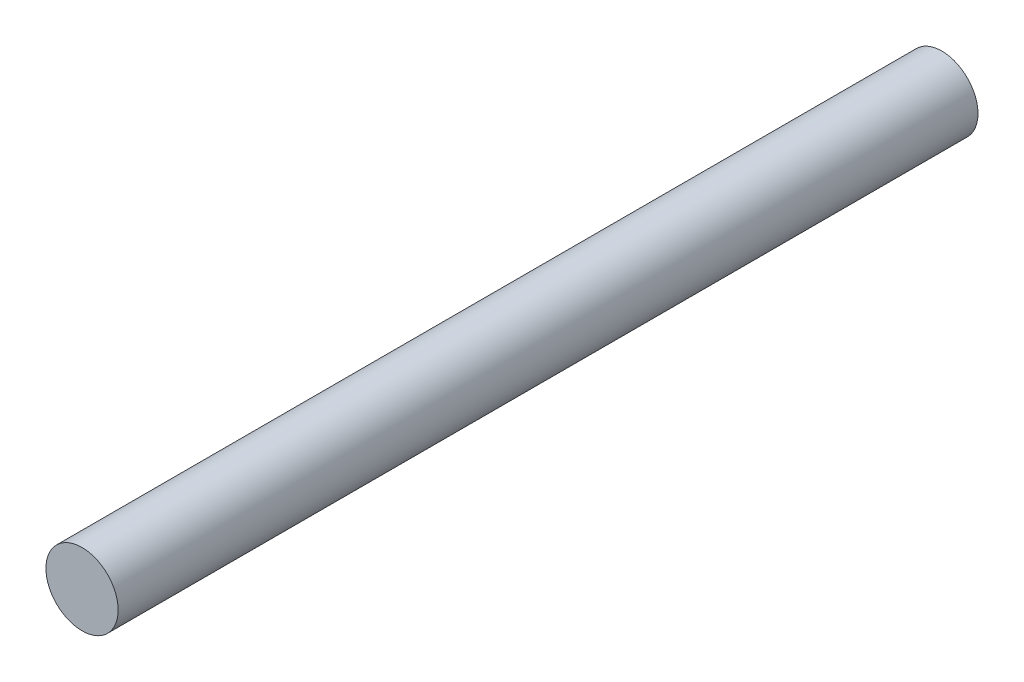
SolidWorks part; units mm, degrees
ref_plane "Piano frontale" through (0, 0, 0) normal (1, 0, 0) x (0, 1, 0)
ref_plane "Piano superiore" through (0, 0, 0) normal (0, 0, 1) x (0, 1, 0)
ref_plane "Piano destro" through (0, 0, 0) normal (0, 1, 0) x (-1, 0, 0)
sketch "Schizzo1" plane through (0, 0, 0) normal (0, 0, 1) x (0, 1, 0)
  circle A0 centre (0, 0) radius 2.1
  dimension "D1" = 4.2
extrude "Estrusione-Estrusione1" add sketch "Schizzo1" along normal blind 50
